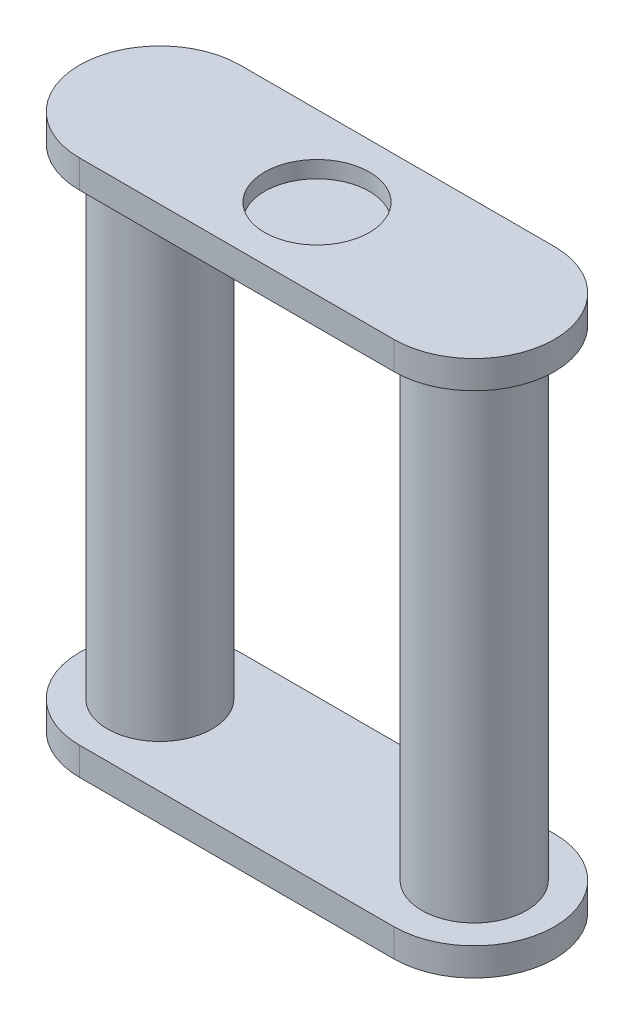
SolidWorks part; units mm, degrees
material "Ductile Iron"
ref_plane "Front Plane" through (0, 0, 0) normal (0, 0, 1) x (1, 0, 0)
ref_plane "Top Plane" through (0, 0, 0) normal (0, 1, 0) x (1, 0, 0)
ref_plane "Right Plane" through (0, 0, 0) normal (1, 0, 0) x (0, 0, -1)
sketch "Sketch1" plane through (0, 0, 0) normal (0, 1, 0) x (1, 0, 0)
  line L0 (0, 0) -> (450, 0)
  line L1 (0, 230) -> (450, 230)
  arc A0 (0, 230) -> (0, 0) centre (0, 115) ccw
  arc A1 (450, 0) -> (450, 230) centre (450, 115) ccw
  dimension "D2" = 230
  dimension "D3" = 230
  dimension "D1" = 450
extrude "Boss-Extrude1" add sketch "Sketch1" along normal blind 40
sketch "Sketch2" plane through (0, 40, 0) normal (0, 1, 0) x (1, 0, 0)
  circle A0 centre (0, 115) radius 75
  circle A1 centre (450, 115) radius 75
  dimension "D1" = 150
  dimension "D2" = 150
extrude "Boss-Extrude2" add sketch "Sketch2" along normal blind 688
ref_plane "Plane1" through (0, 384, 0) normal (0, 1, 0) x (1, 0, 0)
mirror "Mirror1" about plane through (0, 384, 0) normal (0, 1, 0) of "Boss-Extrude1"
sketch "Sketch3" plane through (0, 768, 0) normal (0, 1, 0) x (1, 0, 0)
  line L1 (0, 0) -> (450, 0) construction
  circle A0 centre (225, 115) radius 75
  dimension "D1" = 150
  dimension "D2" = 115
extrude "Boss-Extrude3" add sketch "Sketch3" along normal blind 1
mirror "Mirror2" about plane through (0, 384, 0) normal (0, 1, 0) of "Boss-Extrude3"
sketch "Sketch5" plane through (0, 769, 0) normal (0, 1, 0) x (1, 0, 0)
  circle A0 centre (225, 115) radius 75
extrude "Cut-Extrude1" cut sketch "Sketch5" against normal blind 25
mirror "Mirror3" about plane through (0, 384, 0) normal (0, 1, 0) of "Cut-Extrude1"
